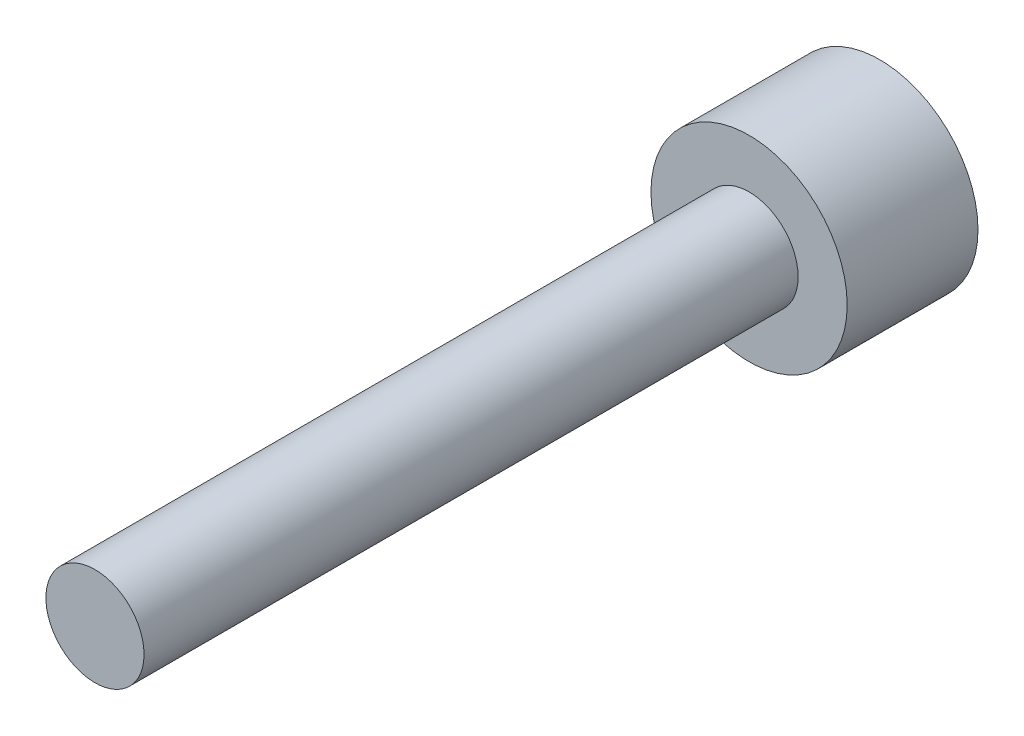
SolidWorks part; units mm, degrees
material "普通碳钢"
ref_plane "前视基准面" through (0, 0, 0) normal (0, 0, 1) x (1, 0, 0)
ref_plane "上视基准面" through (0, 0, 0) normal (0, 1, 0) x (1, 0, 0)
ref_plane "右视基准面" through (0, 0, 0) normal (1, 0, 0) x (0, 0, -1)
sketch "草图1" plane through (0, 0, 0) normal (0, 0, 1) x (1, 0, 0)
  circle A0 centre (0, 0) radius 3
  dimension "D1" = 6
extrude "拉伸1" add sketch "草图1" along normal blind 4
sketch "草图2" plane through (0, 0, 4) normal (0, 0, 1) x (1, 0, 0)
  circle A0 centre (0, 0) radius 1.5
  dimension "D1" = 3
extrude "拉伸2" add sketch "草图2" along normal blind 20
